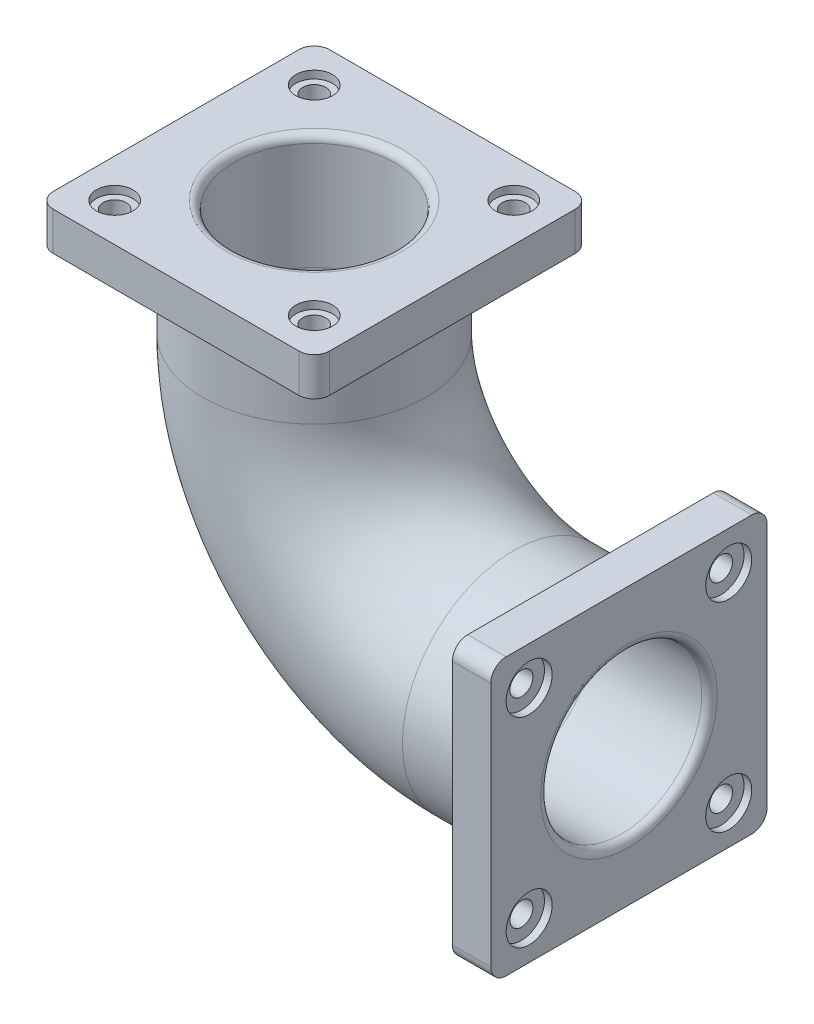
SolidWorks part; units mm, degrees
ref_plane "Front Plane" through (0, 0, 0) normal (0, 0, 1) x (1, 0, 0)
ref_plane "Top Plane" through (0, 0, 0) normal (0, 1, 0) x (1, 0, 0)
ref_plane "Right Plane" through (0, 0, 0) normal (1, 0, 0) x (0, 0, -1)
sketch "Sketch1" plane through (0, 0, 0) normal (0, 1, 0) x (1, 0, 0)
  line L0 (-130, 130) -> (-130, -130) construction
  line L1 (180, 180) -> (-180, 180)
  line L2 (180, 180) -> (180, -180)
  line L3 (180, -180) -> (-180, -180)
  line L4 (-180, 180) -> (-180, -180)
  line L7 (-130, 130) -> (130, 130) construction
  line L8 (-130, -130) -> (130, -130) construction
  line L9 (130, 130) -> (130, -130) construction
  line L10 (0, 180) -> (0, -180) construction
  line L11 (-180, 0) -> (180, 0) construction
  circle A0 centre (-130, 130) radius 15
  circle A1 centre (130, 130) radius 15
  circle A2 centre (130, -130) radius 15
  circle A3 centre (-130, -130) radius 15
  point P0 (0, 0)
  point P18 (0, 0)
  point P25 (0, 0)
  dimension "D6" = 30
  dimension "D1" = 360
  dimension "D2" = 260
  dimension "D3" = 260
  dimension "D4" = 130
  dimension "D5" = 130
  dimension "D7" = 4
extrude "Boss-Extrude1" add sketch "Sketch1" along normal blind 50
fillet "Fillet1" radius 20 4 edges at (-180, 25, -180) (-180, 25, 180) (180, 25, -180) (180, 25, 180)
sketch "Sketch2" plane through (0, 50, 0) normal (0, 1, 0) x (1, 0, 0)
  circle A0 centre (0, 0) radius 105
  dimension "D1" = 210
extrude "Cut-Extrude1" cut sketch "Sketch2" against normal blind 50
sketch "Sketch3" plane through (0, 50, 0) normal (0, 1, 0) x (1, 0, 0)
  line L1 (130, 130) -> (-130, 130) construction
  line L2 (130, 130) -> (130, -130) construction
  line L3 (130, -130) -> (-130, -130) construction
  line L4 (-130, 130) -> (-130, -130) construction
  line L5 (130, 130) -> (-130, -130) construction
  line L6 (130, -130) -> (-130, 130) construction
  circle A0 centre (-130, 130) radius 23.8599
  circle A1 centre (130, 130) radius 23.8599
  circle A2 centre (130, -130) radius 23.8599
  circle A3 centre (-130, -130) radius 23.8599
  point P0 (0, 0)
  dimension "D1" = 47.7197
  dimension "D2" = 4
extrude "Cut-Extrude2" cut sketch "Sketch3" against normal blind 10
ref_plane "Plane1" through (0, 0, 0) normal (0, 0, 1) x (1, 0, 0)
sketch "Sketch4" plane through (0, 0, 0) normal (0, 0, 1) x (1, 0, 0)
  line L0 (0, 50) -> (0, -100)
  line L1 (-160, 50) -> (160, 50) construction
  line L2 (260, -360) -> (410, -360)
  line L4 (198, 0) -> (-198, 0) construction
  arc A0 (260, -360) -> (0, -100) centre (260, -100) cw
  dimension "D1" = 260
  dimension "D2" = 150
sketch "Sketch5" plane through (0, 0, 0) normal (0, 1, 0) x (1, 0, 0)
  circle A0 centre (0, 0) radius 145
sweep "Sweep-Thin1" add profiles "Sketch5" path "Sketch4" parameters "D1"=40
sketch "Sketch9" plane through (410, 0, 0) normal (1, 0, 0) x (0, 0, -1)
  line L1 (180, -180) -> (-180, -180)
  line L2 (180, -180) -> (180, -540)
  line L3 (180, -540) -> (-180, -540)
  line L4 (-180, -180) -> (-180, -540)
  line L5 (180, -180) -> (-180, -540) construction
  line L6 (180, -540) -> (-180, -180) construction
  point P0 (0, -360)
  dimension "D1" = 360
extrude "Boss-Extrude2" add sketch "Sketch9" against normal blind 50
fillet "Fillet2" radius 20 4 edges at (385, -180, 180) (385, -540, 180) (385, -540, -180) (385, -180, -180)
sketch "Sketch10" plane through (410, 0, 0) normal (1, 0, 0) x (0, 0, -1)
  line L0 (0, -100) -> (0, -360) construction
  line L1 (160, -180) -> (-160, -180) construction
  line L2 (130, -230) -> (-130, -230)
  line L3 (130, -230) -> (130, -490)
  line L4 (130, -490) -> (-130, -490)
  line L5 (-130, -230) -> (-130, -490)
  line L6 (130, -230) -> (-130, -490) construction
  line L7 (130, -490) -> (-130, -230) construction
  circle A0 centre (0, -360) radius 105
  circle A1 centre (-130, -230) radius 15
  circle A2 centre (130, -230) radius 15
  circle A3 centre (130, -490) radius 15
  circle A4 centre (-130, -490) radius 15
  dimension "D1" = 210
  dimension "D4" = 4
  dimension "D2" = 260
  dimension "D3" = 180
extrude "Cut-Extrude3" cut sketch "Sketch10" against normal blind 50 contours A4 | A1 | A2 | A3 | A0
sketch "Sketch11" plane through (410, 0, 0) normal (1, 0, 0) x (0, 0, -1)
  circle A0 centre (-130, -230) radius 30
  circle A1 centre (130, -230) radius 30
  circle A2 centre (130, -490) radius 30
  circle A3 centre (-130, -490) radius 30
  dimension "D1" = 4
extrude "Cut-Extrude4" cut sketch "Sketch11" against normal blind 10
fillet "Fillet3" radius 10 2 edges at (410, -255, 0) (0, 50, 105)
